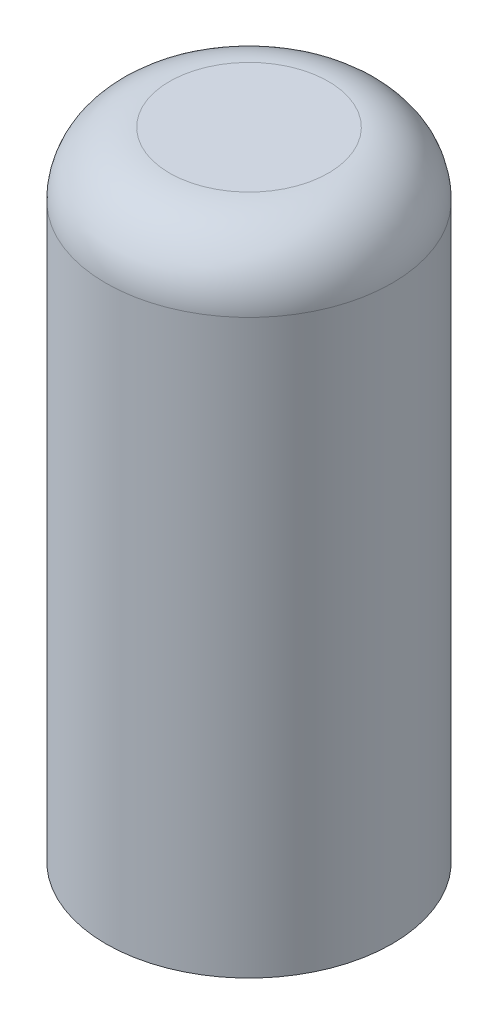
SolidWorks part; units mm, degrees
ref_plane "Ebene vorne" through (0, 0, 0) normal (0, 0, 1) x (1, 0, 0)
ref_plane "Ebene oben" through (0, 0, 0) normal (0, 1, 0) x (1, 0, 0)
ref_plane "Ebene rechts" through (0, 0, 0) normal (1, 0, 0) x (0, 0, -1)
sketch "Skizze1" plane through (0, 0, 0) normal (0, 1, 0) x (1, 0, 0)
  circle A0 centre (0, 0) radius 0.45
  dimension "D1" = 0.9
extrude "Aufsatz-Linear austragen1" add sketch "Skizze1" along normal blind 2 contours A0
fillet "Verrundung1" radius 0.2 1 edges at (0, 2, 0.45)
